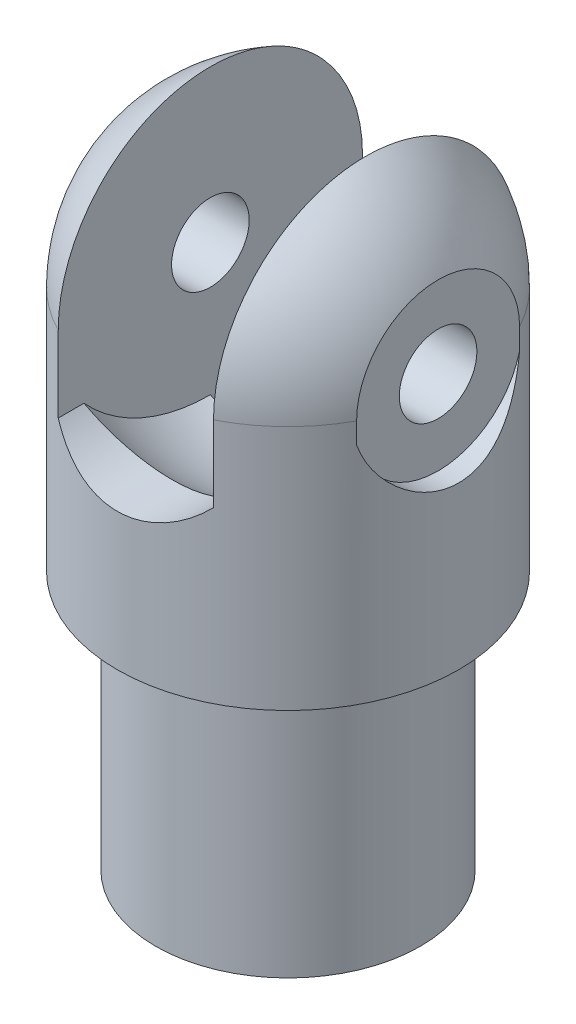
SolidWorks part; units mm, degrees
ref_plane "Front Plane" through (0, 0, 0) normal (0, 0, 1) x (1, 0, 0)
ref_plane "Top Plane" through (0, 0, 0) normal (0, 1, 0) x (1, 0, 0)
ref_plane "Right Plane" through (0, 0, 0) normal (1, 0, 0) x (0, 0, -1)
sketch "Sketch1" plane through (0, 0, 0) normal (0, 1, 0) x (1, 0, 0)
  circle A0 centre (0, 0) radius 12.9921
extrude "Boss-Extrude1" add sketch "Sketch1" along normal blind 25.4 contours A0
sketch "Sketch2" plane through (0, 0, 0) normal (1, 0, 0) x (0, 0, -1)
  line L0 (-16.764, 25.4) -> (-16.764, 49.53)
  line L1 (0, 25.4) -> (-16.764, 25.4)
  line L4 (12.9921, 25.4) -> (-12.9921, 25.4) construction
  line L5 (0, 14.2913) -> (0, -14.2913) construction
  line L6 (0, 25.4) -> (0, 66.294)
  arc A0 (0, 66.294) -> (-16.764, 49.53) centre (0, 49.53) ccw
  dimension "D1" = 33.528
  dimension "D2" = 24.13
revolve "Revolve1" add sketch "Sketch2" angle 360 about L6
sketch "Sketch3" plane through (0, 0, 0) normal (1, 0, 0) x (0, 0, -1)
  line L2 (16.764, 49.53) -> (-16.764, 49.53) construction
  circle A2 centre (0, 49.53) radius 3.81
extrude "Cut-Extrude1" cut sketch "Sketch3" against normal through all both and the other way through all
sketch "Sketch4" plane through (0, 0, 0) normal (0, 0, 1) x (1, 0, 0)
  line L0 (16.3253, 49.53) -> (-16.3253, 49.53) construction
  line L1 (-7.62, 32.9954) -> (-7.62, 49.53)
  line L2 (-7.62, 49.53) -> (7.62, 49.53)
  line L3 (7.62, 49.53) -> (7.62, 32.9954)
  arc A0 (-7.62, 32.9954) -> (7.62, 32.9954) centre (0, 49.53) ccw
  dimension "D1" = 15.24
revolve "Cut-Revolve1" cut sketch "Sketch4" angle 270 about L2
sketch "Sketch5" plane through (0, 0, 0) normal (0, 0, 1) x (1, 0, 0)
  line L0 (0, -18.4404) -> (0, 18.4404) construction
  line L1 (7.62, 49.53) -> (-7.62, 49.53) construction
  line L2 (7.62, 53.34) -> (-7.62, 53.34)
  line L3 (-7.62, 53.34) -> (-7.62, 36.5755)
  line L4 (7.62, 53.34) -> (7.62, 36.5755)
  arc A0 (-7.62, 36.5755) -> (7.62, 36.5755) centre (0, 53.34) ccw
  dimension "D1" = 3.81
revolve "Cut-Revolve2" cut sketch "Sketch5" angle 270 about L2
ref_plane "Plane1" through (16.764, 0, 0) normal (1, 0, 0) x (0, 0, -1)
sketch "Sketch6" plane through (16.764, 0, 0) normal (1, 0, 0) x (0, 0, -1)
  circle A0 centre (0, 49.53) radius 8.255
extrude "Cut-Extrude2" cut sketch "Sketch6" against normal blind 2.032
mirror "Mirror1" about plane through (0, 0, 0) normal (1, 0, 0) of "Cut-Extrude2"
sketch "Sketch7" plane through (0, 0, 0) normal (0, 0, 1) x (1, 0, 0)
  line L0 (0, -18.4404) -> (0, 18.4404) construction
  line L1 (-7.62, 49.53) -> (-7.62, 42.064)
  line L2 (7.62, 49.53) -> (7.62, 42.064)
  line L3 (-7.62, 49.53) -> (7.62, 49.53)
  arc A0 (-7.62, 42.064) -> (7.62, 42.064) centre (0, 49.53) ccw
extrude "Cut-Extrude3" cut sketch "Sketch7" along normal blind 24.638
